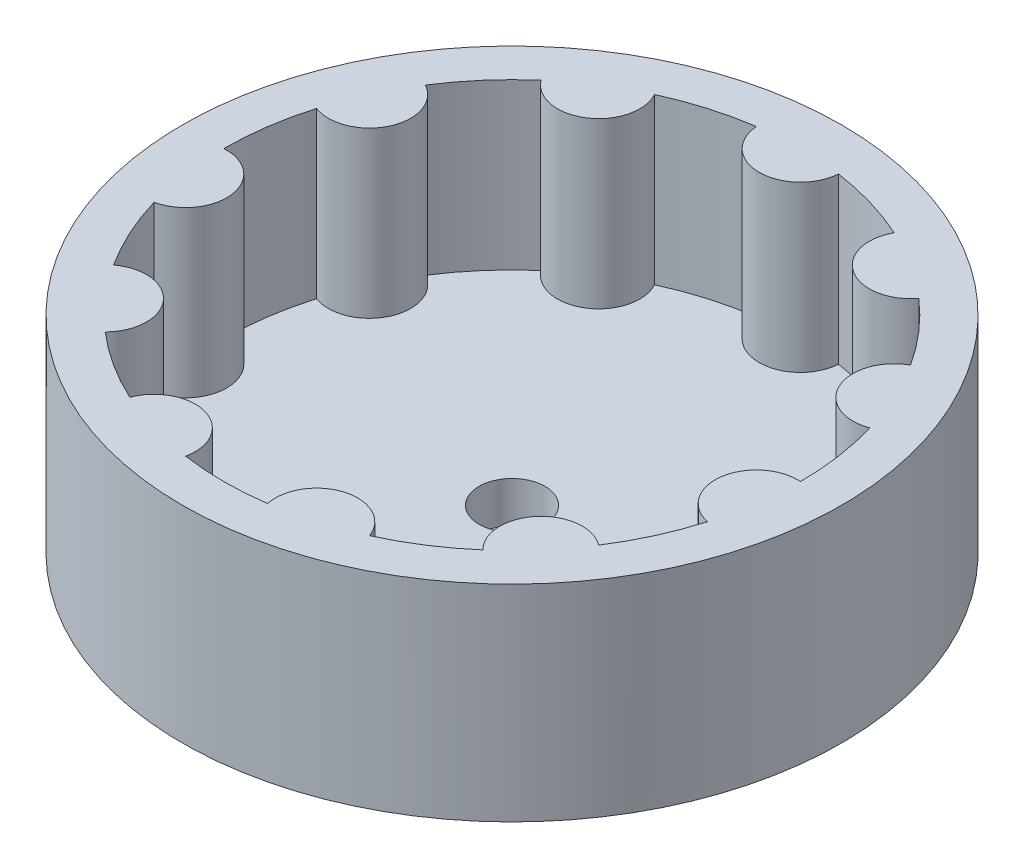
SolidWorks part; units mm, degrees
ref_plane "Front Plane" through (0, 0, 0) normal (0, 0, 1) x (1, 0, 0)
ref_plane "Top Plane" through (0, 0, 0) normal (0, 1, 0) x (1, 0, 0)
ref_plane "Right Plane" through (0, 0, 0) normal (1, 0, 0) x (0, 0, -1)
sketch "Sketch1" plane through (0, 0, 0) normal (0, 1, 0) x (1, 0, 0)
  circle A0 centre (0, 0) radius 35
  circle A1 centre (0, 35) radius 5
  circle A2 centre (18.9224, 29.4439) radius 5
  circle A3 centre (31.8371, 14.5395) radius 5
  circle A4 centre (34.6438, -4.981) radius 5
  circle A5 centre (26.4512, -22.9201) radius 5
  circle A6 centre (9.8606, -33.5823) radius 5
  circle A7 centre (-9.8606, -33.5823) radius 5
  circle A8 centre (-26.4512, -22.9201) radius 5
  circle A9 centre (-34.6438, -4.981) radius 5
  circle A10 centre (-31.8371, 14.5395) radius 5
  circle A11 centre (-18.9224, 29.4439) radius 5
  point P28 (0, 0)
  dimension "D1" = 70
  dimension "D2" = 11
  dimension "D3" = 10
extrude "Boss-Extrude1" add sketch "Sketch1" along normal blind 20 contours A0 A1 | A0 A1 | A0 A2 | A0 A2 | A0 A3 | A0 A3 | A0 A4 | A0 A4 | A0 A5 | A0 A5 | A0 A6 | A0 A6 | A0 A7 | A0 A7 | A0 A8 | A0 A8 | A0 A9 | A0 A9 | A0 A10 | A0 A10 | A0 A11 | A0 A11
sketch "Sketch2" plane through (0, 0, 0) normal (0, 1, 0) x (1, 0, 0)
  circle A0 centre (0, 0) radius 35
  circle A1 centre (0, 0) radius 4
extrude "Boss-Extrude2" add sketch "Sketch2" against normal blind 5
sketch "Sketch3" plane through (0, 20, 0) normal (0, 1, 0) x (1, 0, 0)
  line L0 (0, 35) -> (0, 38)
  line L1 (0, 38) -> (1.0607, 36.9393)
  line L2 (1.0607, 36.9393) -> (-1.0607, 36.9393)
  line L3 (-1.0607, 36.9393) -> (0, 38)
  line L4 (0.25, 35) -> (0.25, 38)
  line L5 (-0.25, 35) -> (-0.25, 38)
  line L6 (-0.25, 35) -> (0.25, 35)
  dimension "D1" = 0.25
  dimension "D2" = 0.25
extrude "Cut-Extrude1" cut sketch "Sketch3" against normal blind 0.1 contours L2 L5 L3 | L5 L2 L0 L3 | L2 L4 L1 L0 | L4 L2 L1 | L0 L6 L4 L2 | L5 L6 L0 L2
sketch "Sketch4" plane through (0, -5, 0) normal (0, -1, 0) x (1, 0, 0)
  circle A0 centre (0, 0) radius 35
  circle A1 centre (0, 0) radius 40
  circle A2 centre (0, 0) radius 45
  circle M2 centre (0, 0) radius 35
  dimension "D1" = 90
extrude "Boss-Extrude4" add sketch "Sketch4" against normal blind 5 contours A1 M2
sketch "Sketch5" plane through (0, 0, 0) normal (0, 1, 0) x (1, 0, 0)
  circle A0 centre (0, 0) radius 35
  circle A1 centre (0, 0) radius 40
extrude "Boss-Extrude5" add sketch "Sketch5" along normal blind 20
